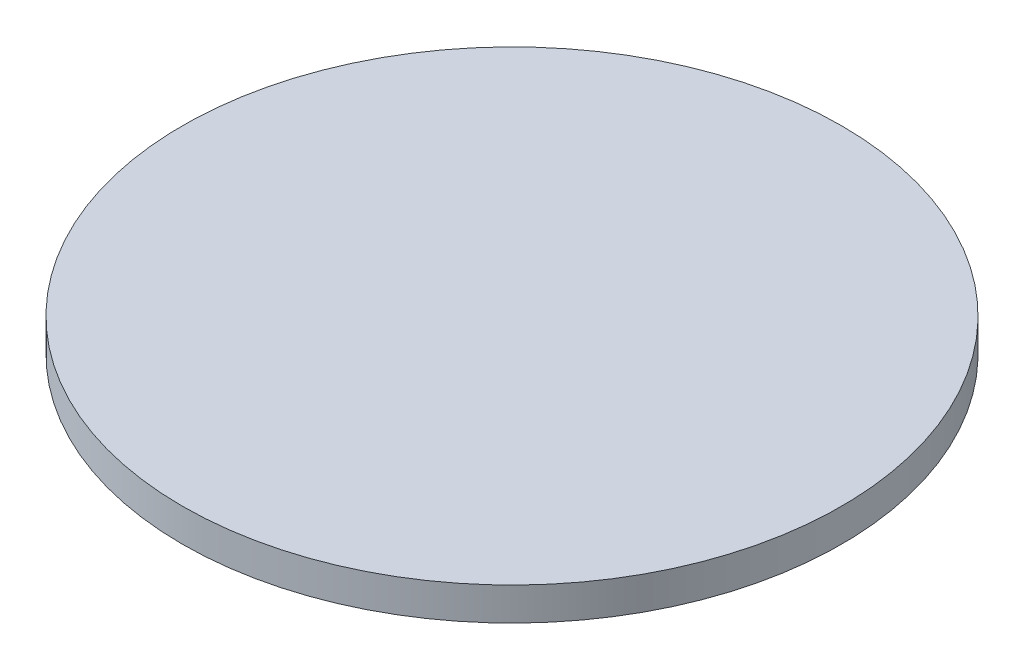
SolidWorks part; units mm, degrees
ref_plane "Front Plane" through (0, 0, 0) normal (0, 0, 1) x (1, 0, 0)
ref_plane "Top Plane" through (0, 0, 0) normal (0, 1, 0) x (1, 0, 0)
ref_plane "Right Plane" through (0, 0, 0) normal (1, 0, 0) x (0, 0, -1)
sketch "Sketch1" plane through (0, 0, 0) normal (0, 1, 0) x (1, 0, 0)
  circle A0 centre (0, 0) radius 5
  dimension "D1" = 10
extrude "Boss-Extrude1" add sketch "Sketch1" along normal blind 0.5
